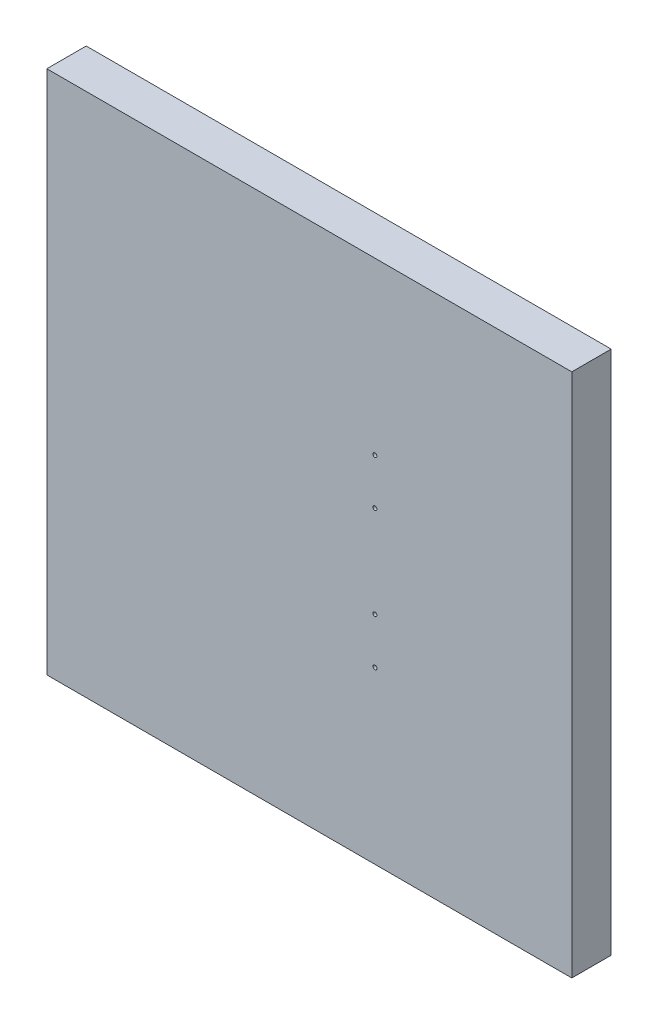
SolidWorks part; units mm, degrees
ref_plane "Plan de face" through (0, 0, 0) normal (0, 0, 1) x (1, 0, 0)
ref_plane "Plan de dessus" through (0, 0, 0) normal (0, 1, 0) x (1, 0, 0)
ref_plane "Plan de droite" through (0, 0, 0) normal (1, 0, 0) x (0, 0, -1)
sketch "Esquisse1" plane through (0, 0, 0) normal (0, 0, 1) x (1, 0, 0)
  line L1 (-200, -200) -> (200, -200)
  line L2 (-200, -200) -> (-200, 200)
  line L3 (-200, 200) -> (200, 200)
  line L4 (200, -200) -> (200, 200)
  line L5 (-200, -200) -> (200, 200) construction
  line L6 (-200, 200) -> (200, -200) construction
  point P0 (0, 0)
  dimension "D1" = 400
  dimension "D2" = 400
extrude "Extrusion1" add sketch "Esquisse1" along normal blind 30
hole_wizard "Trou taraudé M32" positions "Esquisse3D2" profile "Esquisse4" tap size "M3" standard "ISO" end condition through all
sketch3d "Esquisse3D2"
  line L0 (-200, -200, 30) -> (200, -200, 30) construction
  line L1 (200, -200, 30) -> (200, 200, 30) construction
  point P0 (50, 70, 30)
  point P7 (-277.5198, -174.4377, 0)
  point P8 (-220.0328, -124.1657, 0)
  dimension "D1" = 270
  dimension "D2" = 150
sketch "Esquisse4" plane through (50, 70, 30) normal (1, 0, 0) x (0, -1, 0)
  line L0 (0, 0) -> (0, 30)
  line L1 (0, 30) -> (1.5, 30)
  line L2 (1.5, 30) -> (1.5, 0)
  line L5 (1.5, 0) -> (0, 0)
  line L11 (0, -6.35) -> (0, 107.95) construction
  dimension "Diamètre principal du filetage" = 3
  dimension "Profondeur du trou pour taraudage jusqu'au prochain" = 30
pattern_linear "Répétition linéaire1" count 5 spacing 35 along (0, -1, 0) skipping (2, 0) of "Trou taraudé M32"
